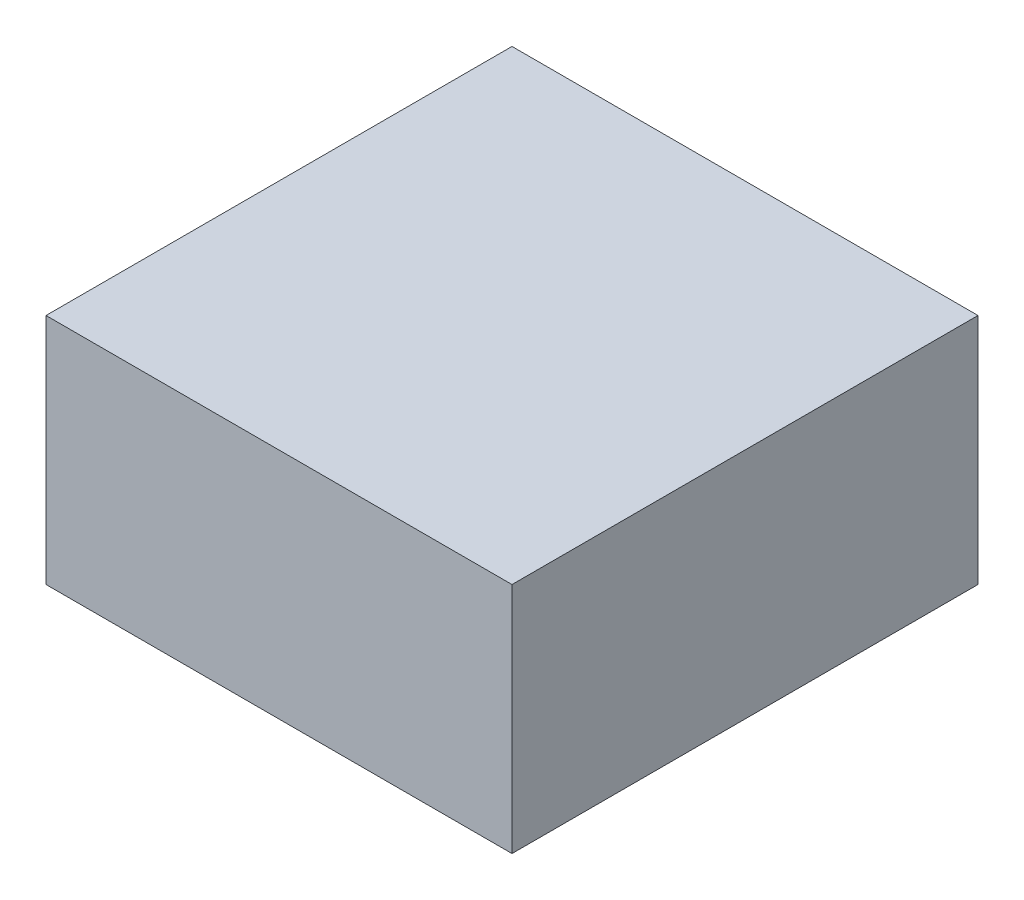
SolidWorks part; units mm, degrees
material "1060 Alloy"
ref_plane "Front Plane" through (0, 0, 0) normal (0, 0, 1) x (1, 0, 0)
ref_plane "Top Plane" through (0, 0, 0) normal (0, 1, 0) x (1, 0, 0)
ref_plane "Right Plane" through (0, 0, 0) normal (1, 0, 0) x (0, 0, -1)
sketch "Sketch1" plane through (0, 0, 0) normal (0, 1, 0) x (1, 0, 0)
  line L1 (-12.7, -12.7) -> (12.7, -12.7)
  line L2 (-12.7, -12.7) -> (-12.7, 12.7)
  line L3 (-12.7, 12.7) -> (12.7, 12.7)
  line L4 (12.7, -12.7) -> (12.7, 12.7)
  line L5 (-12.7, -12.7) -> (12.7, 12.7) construction
  line L6 (-12.7, 12.7) -> (12.7, -12.7) construction
  point P0 (0, 0)
  dimension "D1" = 25.4
extrude "Boss-Extrude1" add sketch "Sketch1" along normal blind 12.7
